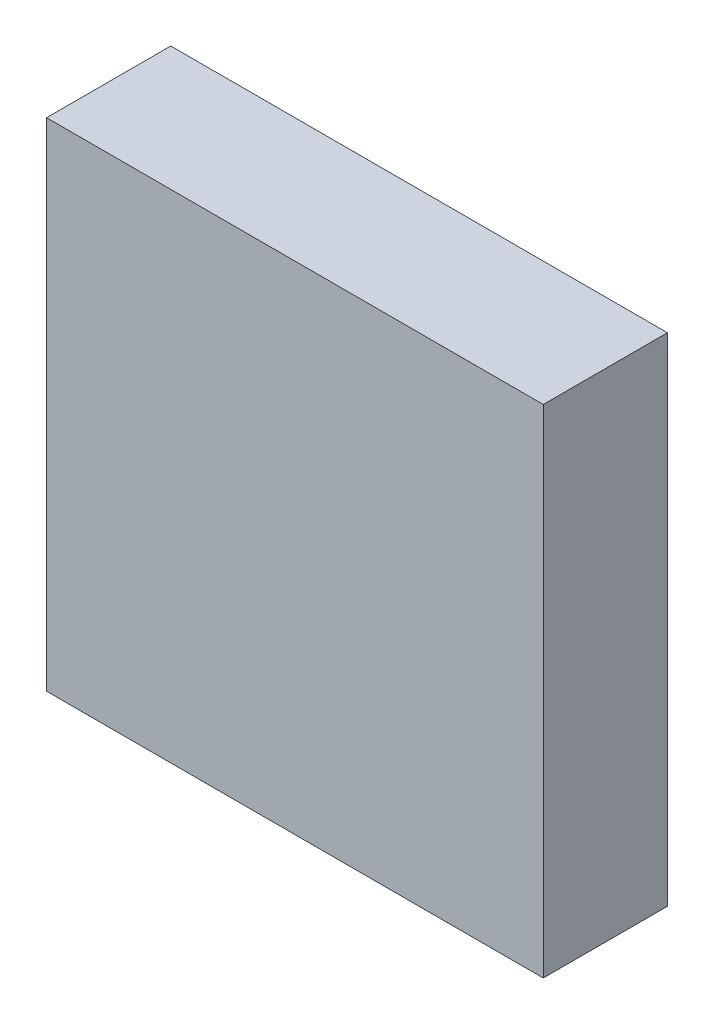
SolidWorks part; units mm, degrees
ref_plane "Front Plane" through (0, 0, 0) normal (0, 0, 1) x (1, 0, 0)
ref_plane "Top Plane" through (0, 0, 0) normal (0, 1, 0) x (1, 0, 0)
ref_plane "Right Plane" through (0, 0, 0) normal (1, 0, 0) x (0, 0, -1)
sketch "Sketch1" plane through (0, 0, 0) normal (0, 0, 1) x (1, 0, 0)
  line L1 (6.4768, -2.1052) -> (-6.2232, -2.1052)
  line L2 (6.4768, -2.1052) -> (6.4768, 10.5948)
  line L3 (6.4768, 10.5948) -> (-6.2232, 10.5948)
  line L4 (-6.2232, -2.1052) -> (-6.2232, 10.5948)
  dimension "D1" = 12.7
  dimension "D2" = 12.7
extrude "Boss-Extrude1" add sketch "Sketch1" along normal blind 3.175
